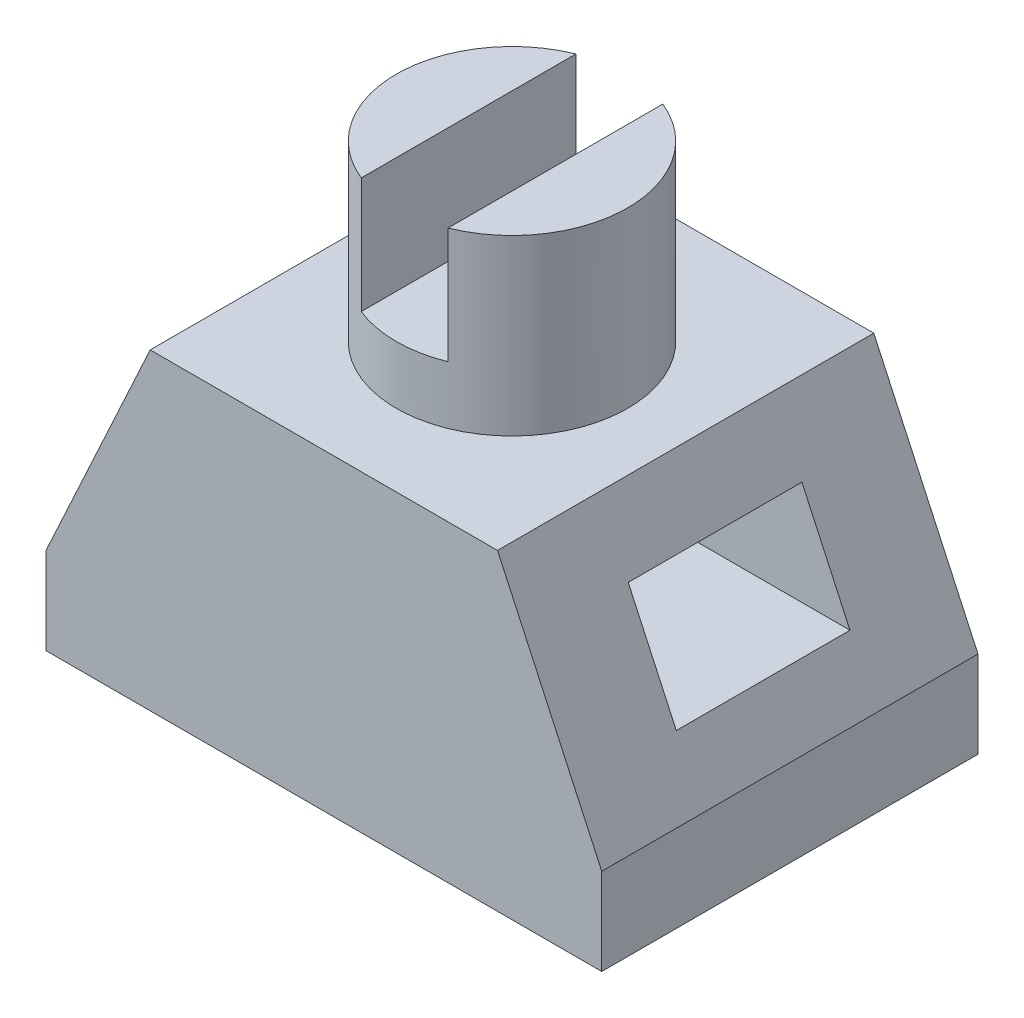
SolidWorks part; units mm, degrees
material "Сталь"
ref_plane "Спереди" through (0, 0, 0) normal (0, 0, 1) x (1, 0, 0)
ref_plane "Сверху" through (0, 0, 0) normal (0, 1, 0) x (1, 0, 0)
ref_plane "Справа" through (0, 0, 0) normal (1, 0, 0) x (0, 0, -1)
sketch "Эскиз1" plane through (0, 0, 0) normal (0, 0, 1) x (1, 0, 0)
  line L0 (-30, 27) -> (-48, -12)
  line L1 (-48, -27) -> (48, -27)
  line L2 (-48, -27) -> (-48, 27) construction
  line L3 (-48, 27) -> (48, 27) construction
  line L4 (48, -27) -> (48, 27) construction
  line L5 (-48, -27) -> (48, 27) construction
  line L6 (-48, 27) -> (48, -27) construction
  line L7 (30, 27) -> (48, -12)
  line L8 (-48, -12) -> (-48, -27)
  line L9 (48, -12) -> (48, -27)
  line L10 (30, 27) -> (-30, 27)
  point P0 (0, 0)
  dimension "D1" = 96
  dimension "D2" = 54
  dimension "D3" = 15
  dimension "D4" = 60
extrude "Бобышка-Вытянуть2" add sketch "Эскиз1" along normal mid plane 65
sketch "Эскиз2" plane through (0, 0, 0) normal (1, 0, 0) x (0, 0, -1)
  line L0 (0, 27) -> (0, -12) construction
  line L1 (-32.5, 27) -> (32.5, 27) construction
  line L2 (-32.5, -12) -> (32.5, -12) construction
  line L3 (-32.5, -27) -> (32.5, -27) construction
  line L4 (-15, -2) -> (15, -2)
  line L5 (-15, -2) -> (-15, 16)
  line L6 (-15, 16) -> (15, 16)
  line L7 (15, -2) -> (15, 16)
  line L8 (-15, -2) -> (15, 16) construction
  line L9 (-15, 16) -> (15, -2) construction
  point P6 (0, 7)
  dimension "D1" = 30
  dimension "D2" = 25
  dimension "D3" = 18
extrude "Вырез-Вытянуть1" cut sketch "Эскиз2" against normal through all and the other way through all
sketch "Эскиз3" plane through (0, 27, 0) normal (0, 1, 0) x (1, 0, 0)
  circle A0 centre (0, 0) radius 20
  dimension "D1" = 40
extrude "Бобышка-Вытянуть3" add sketch "Эскиз3" along normal blind 30
sketch "Эскиз4" plane through (0, 57, 0) normal (0, 1, 0) x (1, 0, 0)
  line L0 (30, 32.5) -> (-30, 32.5) construction
  line L1 (-7.5, -32.5) -> (7.5, -32.5)
  line L2 (-7.5, -32.5) -> (-7.5, 32.5)
  line L3 (-7.5, 32.5) -> (7.5, 32.5)
  line L4 (7.5, -32.5) -> (7.5, 32.5)
  line L5 (-7.5, -32.5) -> (7.5, 32.5) construction
  line L6 (-7.5, 32.5) -> (7.5, -32.5) construction
  point P0 (0, 0)
  dimension "D1" = 15
extrude "Вырез-Вытянуть2" cut sketch "Эскиз4" against normal blind 20
